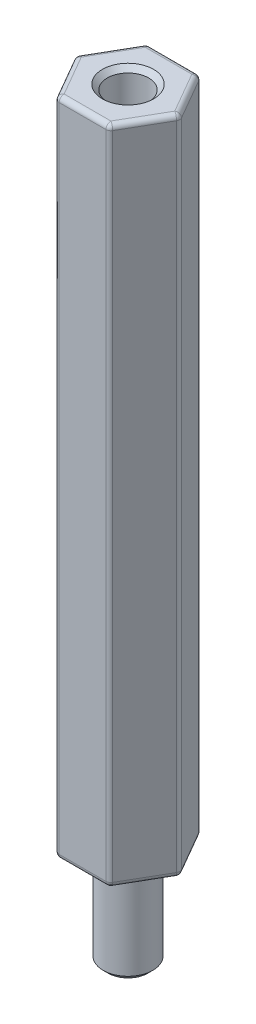
SolidWorks part; units mm, degrees
material "Cast Stainless Steel"
ref_plane "Front Plane" through (0, 0, 0) normal (0, 0, 1) x (1, 0, 0)
ref_plane "Top Plane" through (0, 0, 0) normal (0, 1, 0) x (1, 0, 0)
ref_plane "Right Plane" through (0, 0, 0) normal (1, 0, 0) x (0, 0, -1)
sketch "Sketch1" plane through (0, 0, 0) normal (0, 1, 0) x (1, 0, 0)
  line L1 (-1.5877, 2.75) -> (-3.1754, 0)
  line L2 (-3.1754, 0) -> (-1.5877, -2.75)
  line L3 (-1.5877, -2.75) -> (1.5877, -2.75)
  line L4 (1.5877, -2.75) -> (3.1754, 0)
  line L5 (3.1754, 0) -> (1.5877, 2.75)
  line L6 (1.5877, 2.75) -> (-1.5877, 2.75)
  circle A0 centre (0, 0) radius 2.75 construction
  circle A1 centre (0, 0) radius 1.25
  dimension "D2" = 2.5
  dimension "D1" = 5.5
extrude "Boss-Extrude1" add sketch "Sketch1" along normal blind 40
fillet "Fillet1" radius 0.3 6 edges at (1.5877, 20, -2.75) (3.1754, 20, 0) (-1.5877, 20, -2.75) (-3.1754, 20, 0) (-1.5877, 20, 2.75) (1.5877, 20, 2.75)
fillet "Fillet2" radius 0.3 24 edges at (-1.5645, 0, 2.7098) (-2.3816, 0, 1.375) (-3.129, 0, 0) (-2.3816, 0, -1.375) (-1.5645, 0, -2.7098) (0, 0, -2.75) (1.5645, 0, -2.7098) (2.3816, 0, -1.375) (3.129, 0, 0) (2.3816, 0, 1.375) (1.5645, 0, 2.7098) (-1.5645, 40, 2.7098) (-2.3816, 40, 1.375) (-3.129, 40, 0) (-2.3816, 40, -1.375) (-1.5645, 40, -2.7098) (0, 40, -2.75) (1.5645, 40, -2.7098) (2.3816, 40, -1.375) (3.129, 40, 0) (2.3816, 40, 1.375) (1.5645, 40, 2.7098) (0, 0, 2.75) (0, 40, 2.75)
sketch "Sketch2" plane through (0, 0, 0) normal (0, -1, 0) x (1, 0, 0)
  circle A0 centre (0, 0) radius 1.5
  dimension "D1" = 3
extrude "Boss-Extrude2" add sketch "Sketch2" along normal blind 6
chamfer "Chamfer1" distance 0.3 angle 45 2 edges at (0, 40, 1.25) (0, -6, -1.5)
fillet "Fillet3" radius 0.3 1 edges at (0, 0, 1.5)
